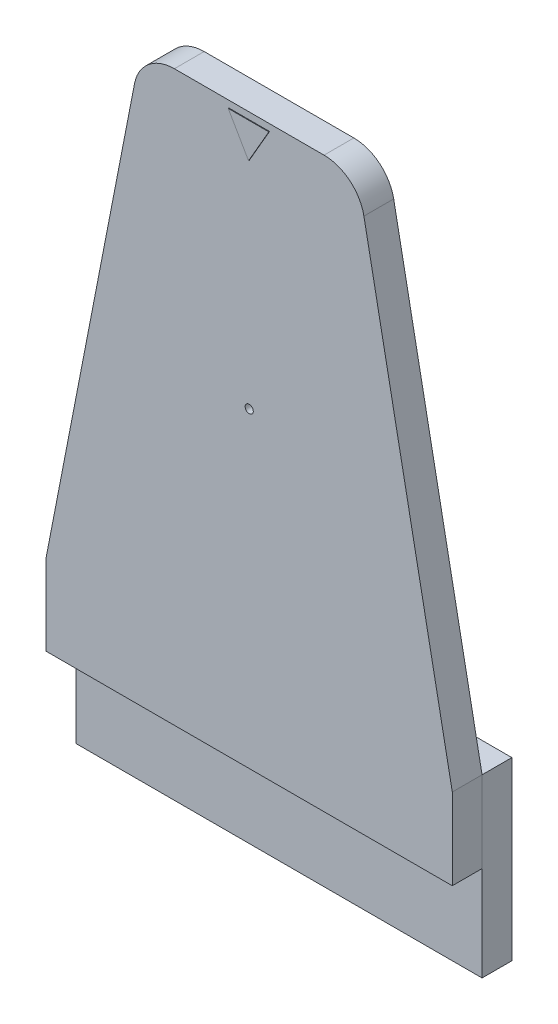
SolidWorks part; units mm, degrees
material "Pin"
ref_plane "Plan de face" through (0, 0, 0) normal (0, 0, 1) x (1, 0, 0)
ref_plane "Plan de dessus" through (0, 0, 0) normal (0, 1, 0) x (1, 0, 0)
ref_plane "Plan de droite" through (0, 0, 0) normal (1, 0, 0) x (0, 0, -1)
sketch "Esquisse1" plane through (0, 0, 0) normal (0, 0, 1) x (1, 0, 0)
  line L0 (150, 60) -> (84.7199, 395.7261)
  line L1 (-150, 0) -> (150, 0)
  line L2 (0, 0) -> (0, 420) construction
  line L3 (-55.2715, 420) -> (55.2715, 420)
  line L4 (150, 0) -> (150, 60)
  line L5 (-150, 0) -> (-150, 60)
  line L6 (-150, 60) -> (-84.7199, 395.7261)
  arc A0 (84.7199, 395.7261) -> (55.2715, 420) centre (55.2715, 390) ccw
  arc A1 (-84.7199, 395.7261) -> (-55.2715, 420) centre (-55.2715, 390) cw
  circle A2 centre (0, 230) radius 3
  point P13 (-80, 420)
  dimension "D1" = 30
  dimension "D7" = 230
  dimension "D8" = 6
  dimension "D2" = 300
  dimension "D3" = 60
  dimension "D4" = 420
  dimension "D5" = 78.996
  dimension "D6" = 160
extrude "Boss.-Extru.1" add sketch "Esquisse1" along normal blind 22
sketch "Esquisse2" plane through (0, 0, 0) normal (0, 0, -1) x (-1, 0, 0)
  line L0 (150, 60) -> (150, 0) construction
  line L1 (-150, 60) -> (150, 60)
  line L2 (-150, 60) -> (-150, -70)
  line L3 (-150, -70) -> (150, -70)
  line L4 (150, 60) -> (150, -70)
  line L5 (150, 0) -> (-150, 0) construction
  dimension "D1" = 70
  dimension "D2" = 130
extrude "Boss.-Extru.2" add sketch "Esquisse2" along normal blind 22 separate body
sketch "Esquisse3" plane through (0, 0, 22) normal (0, 0, 1) x (1, 0, 0)
  line L0 (-15, 415) -> (15, 415)
  line L1 (15, 415) -> (0, 389.0192)
  line L2 (0, 389.0192) -> (-15, 415)
  line L3 (55.2715, 420) -> (-55.2715, 420) construction
  point P2 (0, 0)
  dimension "D1" = 30
  dimension "D2" = 5
extrude "Boss.-Extru.3" add sketch "Esquisse3" along normal blind 0.5 separate body
